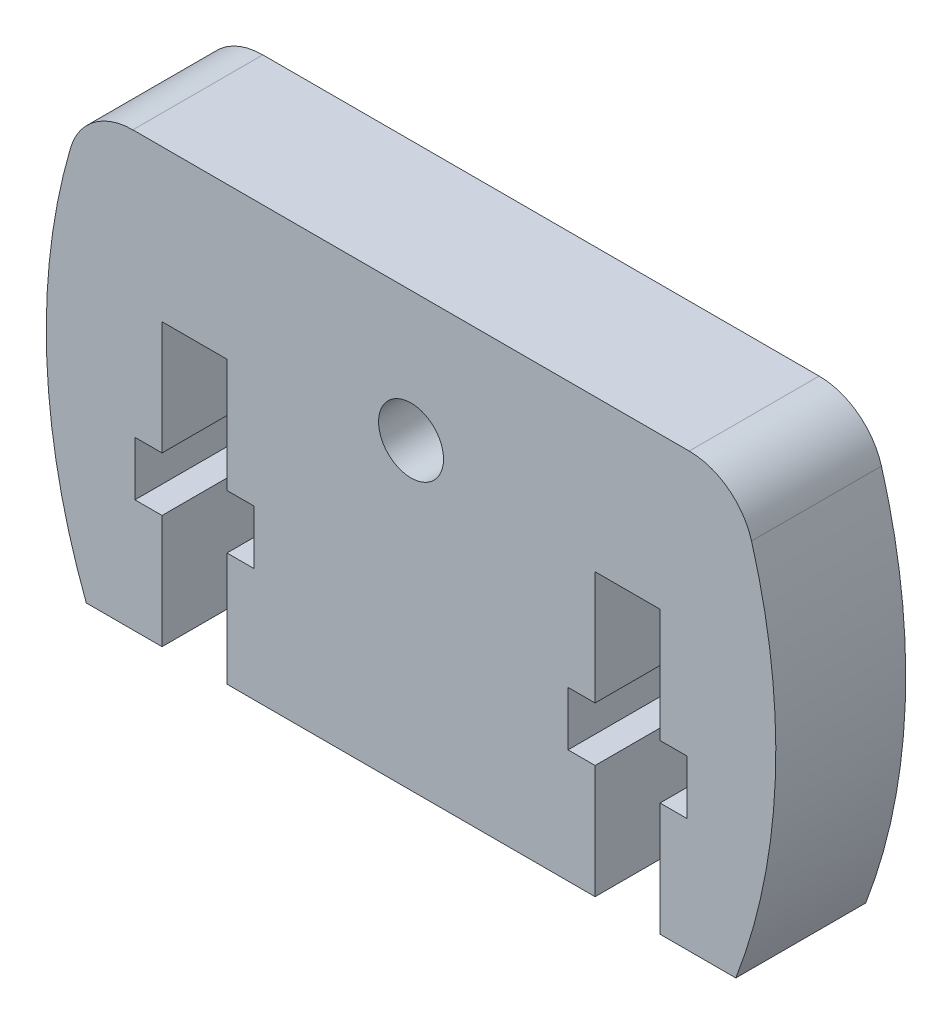
SolidWorks part; units mm, degrees
ref_plane "Спереди" through (0, 0, 0) normal (0, 0, 1) x (1, 0, 0)
ref_plane "Сверху" through (0, 0, 0) normal (0, 1, 0) x (1, 0, 0)
ref_plane "Справа" through (0, 0, 0) normal (1, 0, 0) x (0, 0, -1)
other "Configuration Table"
sketch "Эскиз1" plane through (0, 0, 0) normal (0, 0, 1) x (1, 0, 0)
  line L0 (5, 0) -> (5, 11.0833) construction
  line L1 (0, 0) -> (3.5, 0)
  line L3 (2.1533, 20) -> (27.8467, 20)
  line L5 (3.5, 0) -> (3.5, 5.25)
  line L6 (3.5, 5.25) -> (2.25, 5.25)
  line L7 (2.25, 5.25) -> (2.25, 7.75)
  line L8 (2.25, 7.75) -> (3.5, 7.75)
  line L9 (3.5, 7.75) -> (3.5, 13)
  line L10 (3.5, 13) -> (6.5, 13)
  line L11 (6.5, 7.75) -> (6.5, 13)
  line L12 (7.75, 7.75) -> (6.5, 7.75)
  line L13 (7.75, 5.25) -> (7.75, 7.75)
  line L14 (6.5, 5.25) -> (7.75, 5.25)
  line L15 (6.5, 0) -> (6.5, 5.25)
  line L16 (15, 0) -> (15, 20) construction
  line L17 (25, 0) -> (25, 11.0833) construction
  line L18 (23.5, 0) -> (23.5, 5.25)
  line L19 (23.5, 5.25) -> (22.25, 5.25)
  line L20 (22.25, 5.25) -> (22.25, 7.75)
  line L21 (22.25, 7.75) -> (23.5, 7.75)
  line L22 (23.5, 7.75) -> (23.5, 13)
  line L23 (26.5, 13) -> (23.5, 13)
  line L24 (26.5, 7.75) -> (26.5, 13)
  line L25 (27.75, 7.75) -> (26.5, 7.75)
  line L26 (27.75, 5.25) -> (27.75, 7.75)
  line L27 (26.5, 5.25) -> (27.75, 5.25)
  line L28 (26.5, 0) -> (26.5, 5.25)
  line L29 (6.5, 0) -> (23.5, 0)
  line L30 (26.5, 0) -> (30, 0)
  circle A0 centre (15, 14) radius 1.5
  arc A1 (0, 0) -> (-0.7267, 17.8402) centre (26.1482, 10) cw
  arc A2 (30, 0) -> (30.7267, 17.8402) centre (3.8518, 10) ccw
  arc A3 (27.8467, 20) -> (30.7267, 17.8402) centre (27.8467, 17) cw
  arc A4 (2.1533, 20) -> (-0.7267, 17.8402) centre (2.1533, 17) ccw
  point P15 (5, 13)
  point P36 (25, 13)
  dimension "D8" = 3
  dimension "D10" = 3
  dimension "D1" = 2.5
  dimension "D2" = 3
  dimension "D3" = 5.5
  dimension "D4" = 13
  dimension "D5" = 30
  dimension "D6" = 20
  dimension "D7" = 20
  dimension "D9" = 14
extrude "Бобышка-Вытянуть1" add sketch "Эскиз1" along normal blind 6
